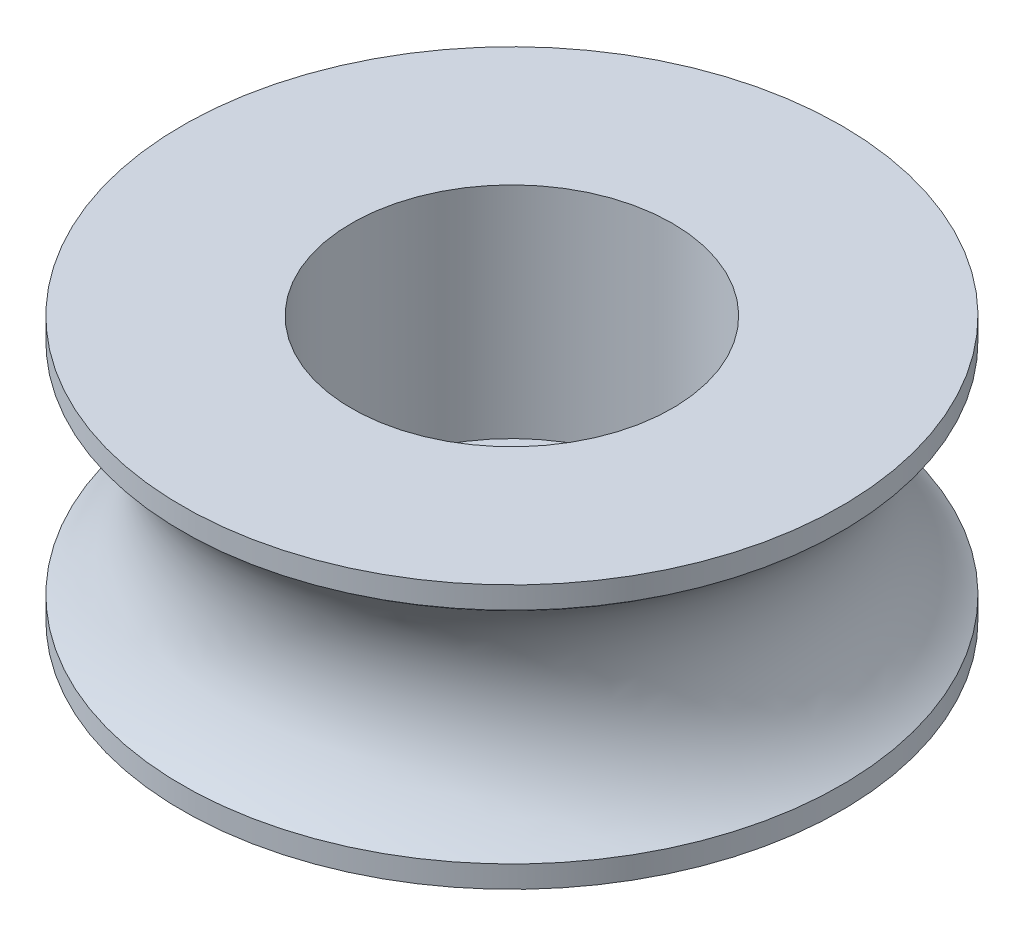
SolidWorks part; units mm, degrees
ref_plane "Ebene vorne" through (0, 0, 0) normal (0, 0, 1) x (1, 0, 0)
ref_plane "Ebene oben" through (0, 0, 0) normal (0, 1, 0) x (1, 0, 0)
ref_plane "Ebene rechts" through (0, 0, 0) normal (1, 0, 0) x (0, 0, -1)
sketch "Sketch1" plane through (0, 0, 0) normal (0, 0, 1) x (1, 0, 0)
  line L0 (0, -6.6295) -> (0, 11.8219) construction
  line L1 (-2.5, 0) -> (-7.5, 0)
  line L2 (-7.5, 0) -> (-7.5, 0.5)
  line L3 (-7.5, 6) -> (-3.65, 6)
  line L4 (-3.65, 6) -> (-3.65, 1)
  line L5 (-3.65, 1) -> (-2.5, 1)
  line L6 (-2.5, 1) -> (-2.5, 0)
  line L7 (-7.5, 5.5) -> (-7.5, 6)
  line L8 (-9.5365, 3) -> (-4.4754, 3) construction
  arc A0 (-7.5, 0.5) -> (-7.5, 5.5) centre (-9.1583, 3) ccw
  dimension "D6" = 3
  dimension "D1" = 7.3
  dimension "D2" = 5
  dimension "D3" = 1
  dimension "D4" = 5
  dimension "D5" = 15
  dimension "D7" = 5
revolve "Revolve1" add sketch "Sketch1" angle 360 about L0
